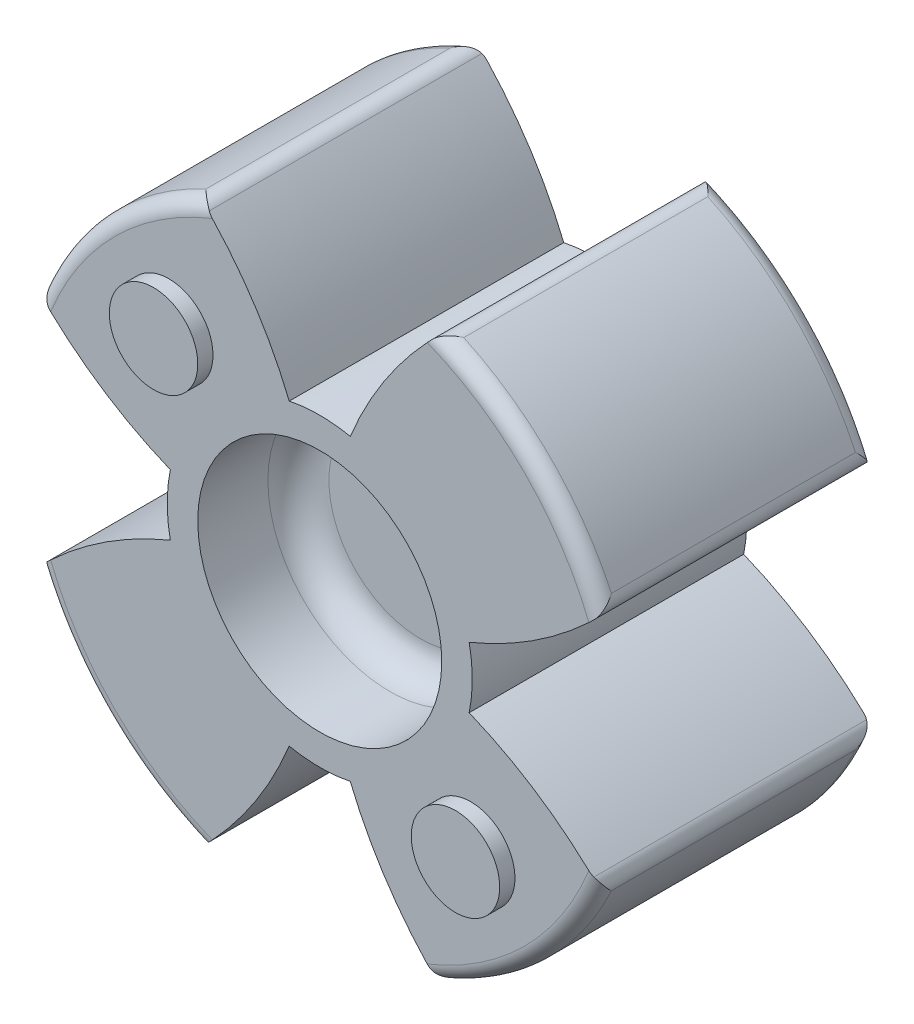
SolidWorks part; units mm, degrees
material "硬質ﾎﾟﾘｳﾚﾀﾝ ﾌｫｰﾑ"
ref_plane "正面" through (0, 0, 0) normal (0, 0, 1) x (1, 0, 0)
ref_plane "平面" through (0, 0, 0) normal (0, 1, 0) x (1, 0, 0)
ref_plane "右側面" through (0, 0, 0) normal (1, 0, 0) x (0, 0, -1)
sketch "ｽｹｯﾁ1" plane through (0, 0, 0) normal (0, 0, 1) x (1, 0, 0)
  arc A17 (-1, -4.899) -> (1, -4.899) centre (0, 0) ccw
  arc A18 (-9.2081, -3.9) -> (-3.9, -9.2081) centre (0, 0) ccw
  arc A19 (-9.2081, 3.9) -> (-4.899, 1) centre (0, 12.931) ccw
  arc A20 (3.9, 9.2081) -> (1, 4.899) centre (12.931, 0) ccw
  arc A21 (9.2081, -3.9) -> (4.899, -1) centre (0, -12.931) ccw
  arc A22 (-3.9, -9.2081) -> (-1, -4.899) centre (-12.931, 0) ccw
  arc A23 (-4.899, -1) -> (-9.2081, -3.9) centre (0, -12.931) ccw
  arc A24 (-1, 4.899) -> (-3.9, 9.2081) centre (-12.931, 0) ccw
  arc A25 (4.899, 1) -> (9.2081, 3.9) centre (0, 12.931) ccw
  arc A26 (1, -4.899) -> (3.9, -9.2081) centre (12.931, 0) ccw
  arc A27 (-3.9, 9.2081) -> (-9.2081, 3.9) centre (0, 0) ccw
  arc A28 (9.2081, 3.9) -> (3.9, 9.2081) centre (0, 0) ccw
  arc A29 (3.9, -9.2081) -> (9.2081, -3.9) centre (0, 0) ccw
  arc A30 (-4.899, 1) -> (-4.899, -1) centre (0, 0) ccw
  arc A31 (1, 4.899) -> (-1, 4.899) centre (0, 0) ccw
  arc A32 (4.899, -1) -> (4.899, 1) centre (0, 0) ccw
  point P6 (3.9, 9.2081)
  point P15 (0, 0)
  point P17 (-3.9, 9.2081)
  dimension "D1" = 10
  dimension "D2" = 20
  dimension "D5" = 4
  dimension "D4" = 2
  dimension "D3" = 7.8
extrude "ﾎﾞｽ - 押し出し1" add sketch "ｽｹｯﾁ1" along normal blind 9
sketch "ｽｹｯﾁ2" plane through (0, 0, 9) normal (0, 0, 1) x (1, 0, 0)
  line L0 (7.0711, -7.0711) -> (-7.0711, 7.0711) construction
  line L1 (-7.0711, -7.0711) -> (7.0711, 7.0711) construction
  arc A2 (-3.9, 9.2081) -> (-9.2081, 3.9) centre (0, 0) ccw construction
  arc A3 (3.9, -9.2081) -> (9.2081, -3.9) centre (0, 0) ccw construction
  circle A4 centre (-4.9497, 4.9497) radius 1.45
  arc A5 (-9.2081, -3.9) -> (-3.9, -9.2081) centre (0, 0) ccw construction
  arc A6 (9.2081, 3.9) -> (3.9, 9.2081) centre (0, 0) ccw construction
  circle A7 centre (4.9497, -4.9497) radius 1.45
  dimension "D1" = 2.9
  dimension "D2" = 14
extrude "ﾎﾞｽ - 押し出し2" add sketch "ｽｹｯﾁ2" along normal blind 0.5
sketch "ｽｹｯﾁ3" plane through (0, 0, 0) normal (0, 0, -1) x (-1, 0, 0)
  line L0 (-7.0711, 7.0711) -> (7.0711, -7.0711) construction
  line L1 (7.0711, 7.0711) -> (-7.0711, -7.0711) construction
  arc A0 (-3.9, 9.2081) -> (-9.2081, 3.9) centre (0, 0) ccw construction
  arc A1 (3.9, -9.2081) -> (9.2081, -3.9) centre (0, 0) ccw construction
  arc A2 (9.2081, 3.9) -> (3.9, 9.2081) centre (0, 0) ccw construction
  arc A3 (-9.2081, -3.9) -> (-3.9, -9.2081) centre (0, 0) ccw construction
  circle A4 centre (-4.9497, 4.9497) radius 1.45
  circle A5 centre (4.9497, -4.9497) radius 1.45
  dimension "D1" = 2.9
  dimension "D2" = 14
extrude "ﾎﾞｽ - 押し出し3" add sketch "ｽｹｯﾁ3" along normal blind 0.5
sketch "ｽｹｯﾁ4" plane through (0, 0, 9) normal (0, 0, 1) x (1, 0, 0)
  circle A0 centre (0, 0) radius 4
  dimension "D1" = 8
extrude "ｶｯﾄ - 押し出し1" cut sketch "ｽｹｯﾁ4" against normal blind 3.3
sketch "ｽｹｯﾁ5" plane through (0, 0, 0) normal (0, 0, -1) x (-1, 0, 0)
  circle A0 centre (0, 0) radius 4 construction
  circle A1 centre (0, 0) radius 4
extrude "ｶｯﾄ - 押し出し2" cut sketch "ｽｹｯﾁ5" against normal blind 3.3
fillet "ﾌｨﾚｯﾄ1" radius 1 2 edges at (4, 0, 5.7) (-4, 0, 3.3)
fillet "ﾌｨﾚｯﾄ2" radius 0.5 16 edges at (-9.2081, -3.9, 4.5) (-7.0711, -7.0711, 9) (-3.9, -9.2081, 4.5) (-7.0711, -7.0711, 0) (3.9, -9.2081, 4.5) (7.0711, -7.0711, 9) (9.2081, -3.9, 4.5) (7.0711, -7.0711, 0) (9.2081, 3.9, 4.5) (7.0711, 7.0711, 9) (3.9, 9.2081, 4.5) (7.0711, 7.0711, 0) (-3.9, 9.2081, 4.5) (-7.0711, 7.0711, 9) (-9.2081, 3.9, 4.5) (-7.0711, 7.0711, 0)
